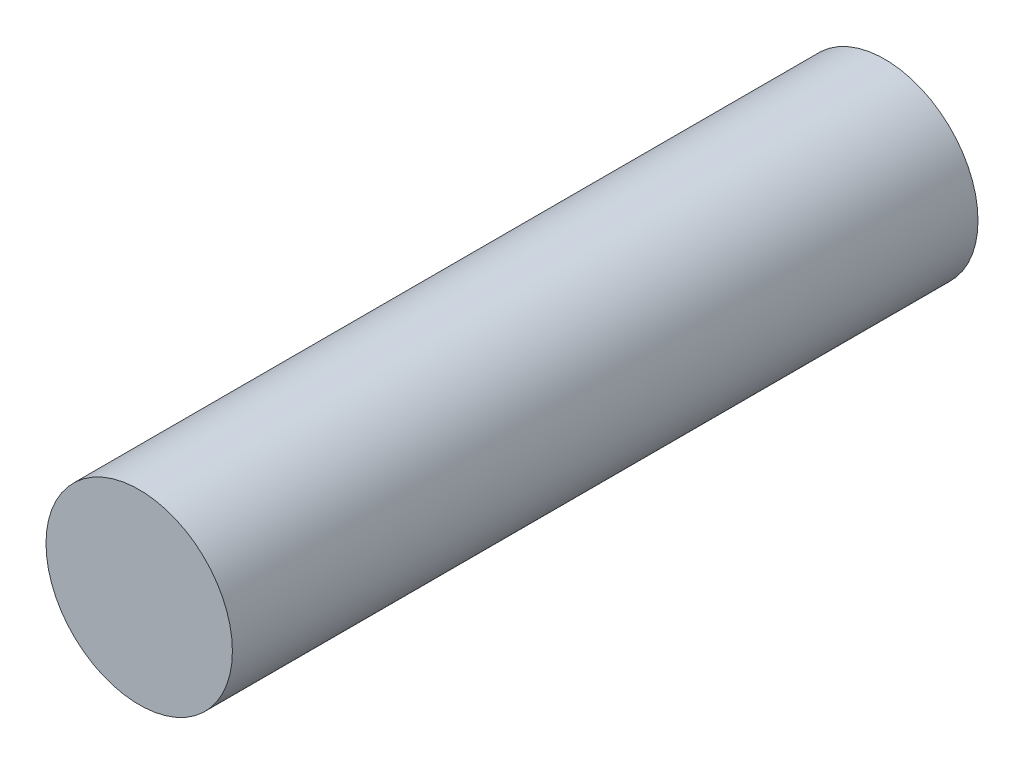
SolidWorks part; units mm, degrees
ref_plane "Plan de face" through (0, 0, 0) normal (0, 0, 1) x (1, 0, 0)
ref_plane "Plan de dessus" through (0, 0, 0) normal (0, 1, 0) x (1, 0, 0)
ref_plane "Plan de droite" through (0, 0, 0) normal (1, 0, 0) x (0, 0, -1)
sketch "Esquisse1" plane through (0, 0, 0) normal (0, 0, 1) x (1, 0, 0)
  circle A0 centre (0, 0) radius 10
  dimension "D1" = 20
extrude "Boss.-Extru.1" add sketch "Esquisse1" along normal blind 80
